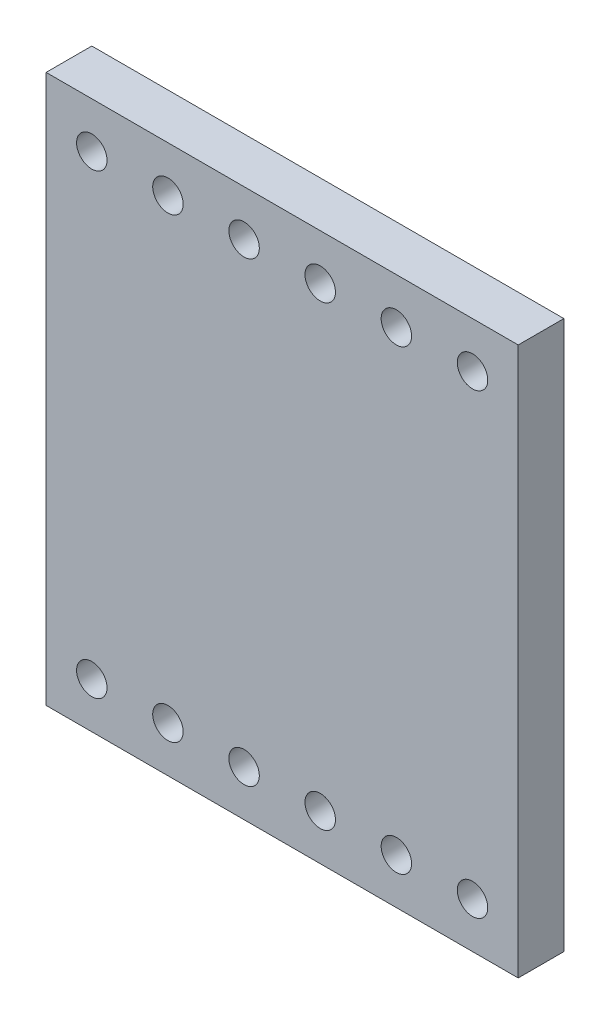
SolidWorks part; units mm, degrees
ref_plane "Front Plane" through (0, 0, 0) normal (1, 0, 0) x (0, 1, 0)
ref_plane "Top Plane" through (0, 0, 0) normal (0, 0, 1) x (0, 1, 0)
ref_plane "Right Plane" through (0, 0, 0) normal (0, 1, 0) x (-1, 0, 0)
sketch "Sketch1" plane through (0, 0, 0) normal (0, 0, 1) x (0, 1, 0)
  line L1 (-9, -7.75) -> (9, -7.75)
  line L2 (-9, -7.75) -> (-9, 7.75)
  line L3 (-9, 7.75) -> (9, 7.75)
  line L4 (9, -7.75) -> (9, 7.75)
  line L5 (-9, -7.75) -> (9, 7.75) construction
  line L6 (-9, 7.75) -> (9, -7.75) construction
  point P0 (0, 0)
  dimension "D1" = 18
  dimension "D2" = 15.5
extrude "Boss-Extrude1" add sketch "Sketch1" along normal mid plane 1.5
sketch "Sketch2" plane through (0, 0, 0.75) normal (0, 0, 1) x (1, 0, 0)
  line L0 (-7.75, -9) -> (7.75, -9) construction
  line L1 (-7.75, 9) -> (-7.75, -9) construction
  line L2 (-6.25, -7.5) -> (-3.75, -7.5) construction
  circle A0 centre (-6.25, -7.5) radius 0.5
  circle A1 centre (-3.75, -7.5) radius 0.5
  circle A2 centre (-1.25, -7.5) radius 0.5
  circle A3 centre (1.25, -7.5) radius 0.5
  circle A4 centre (3.75, -7.5) radius 0.5
  circle A5 centre (6.25, -7.5) radius 0.5
  dimension "D1" = 1
  dimension "D2" = 1.5
  dimension "D3" = 1.5
  dimension "D5" = 2.5
  dimension "D4" = 6
extrude "Cut-Extrude1" cut sketch "Sketch2" against normal blind 1.5
mirror "Mirror1" about plane through (0, 0, 0) normal (0, 1, 0) of "Cut-Extrude1"
